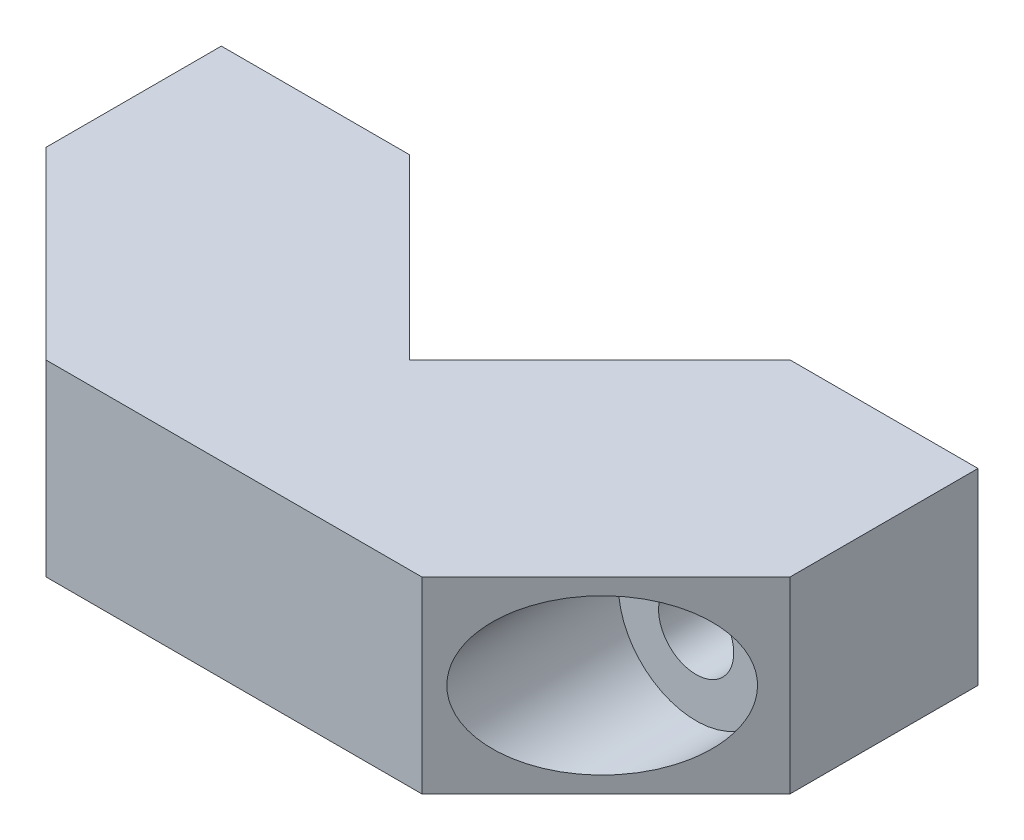
SolidWorks part; units mm, degrees
ref_plane "Front Plane" through (0, 0, 0) normal (0, 0, 1) x (1, 0, 0)
ref_plane "Top Plane" through (0, 0, 0) normal (0, 1, 0) x (1, 0, 0)
ref_plane "Right Plane" through (0, 0, 0) normal (1, 0, 0) x (0, 0, -1)
sketch "Sketch2" plane through (0, 0, 0) normal (0, 1, 0) x (1, 0, 0)
  line L0 (-23.426, 11.8011) -> (-11.4051, -0.2197)
  line L1 (-11.4051, -0.2197) -> (1.4642, 12.6497)
  line L2 (1.4642, 12.6497) -> (14.1642, 12.6497)
  line L3 (14.1642, 12.6497) -> (14.1642, -0.0503)
  line L4 (14.1642, -0.0503) -> (1.7191, -12.4954)
  line L5 (1.7191, -12.4954) -> (-23.6809, -12.4954)
  line L6 (-23.6809, -12.4954) -> (-36.126, -0.0503)
  line L7 (-36.126, -0.0503) -> (-36.126, 11.8011)
  line L8 (-36.126, 11.8011) -> (-23.426, 11.8011)
  dimension "D1" = 18.2
  dimension "D2" = 17
  dimension "D3" = 12.7
  dimension "D4" = 135
  dimension "D5" = 25.4
extrude "Boss-Extrude1" add sketch "Sketch2" along normal blind 12.7
sketch "Sketch3" plane through (0, 0, -11.8011) normal (0, 0, -1) x (-1, 0, 0)
  line L0 (-14.1642, 6.35) -> (36.126, 6.35) construction
  line L1 (-14.1642, 12.7) -> (-14.1642, 0) construction
  line L2 (36.126, 12.7) -> (36.126, 0) construction
  line L3 (29.776, 12.7) -> (29.776, 0) construction
  line L4 (23.426, 12.7) -> (36.126, 12.7) construction
  line L5 (23.426, 0) -> (36.126, 0) construction
  line L6 (-7.8142, 12.7) -> (-7.8142, 0) construction
  line L7 (-14.1642, 12.7) -> (-1.4642, 12.7) construction
  line L8 (-14.1642, 0) -> (-1.4642, 0) construction
  circle A3 centre (-7.8142, 6.35) radius 2.54
  circle A4 centre (29.776, 6.35) radius 2.54
  dimension "D1" = 5.08
extrude "Cut-Extrude3" cut sketch "Sketch3" against normal blind 12.7 from surface at 0.8485 starting at face at (7.8142, 6.35, -12.6497)
sketch "Sketch4" plane through (0, 0, 0.0503) normal (0, 0, -1) x (-1, 0, 0)
  circle A0 centre (-7.8142, 6.35) radius 5.25
  circle A1 centre (29.776, 6.35) radius 5.25
  circle A2 centre (-7.8142, 6.35) radius 2.54 construction
  circle A3 centre (29.776, 6.35) radius 2.54 construction
  dimension "D1" = 10.5
extrude "Cut-Extrude4" cut sketch "Sketch4" against normal blind 12.7
